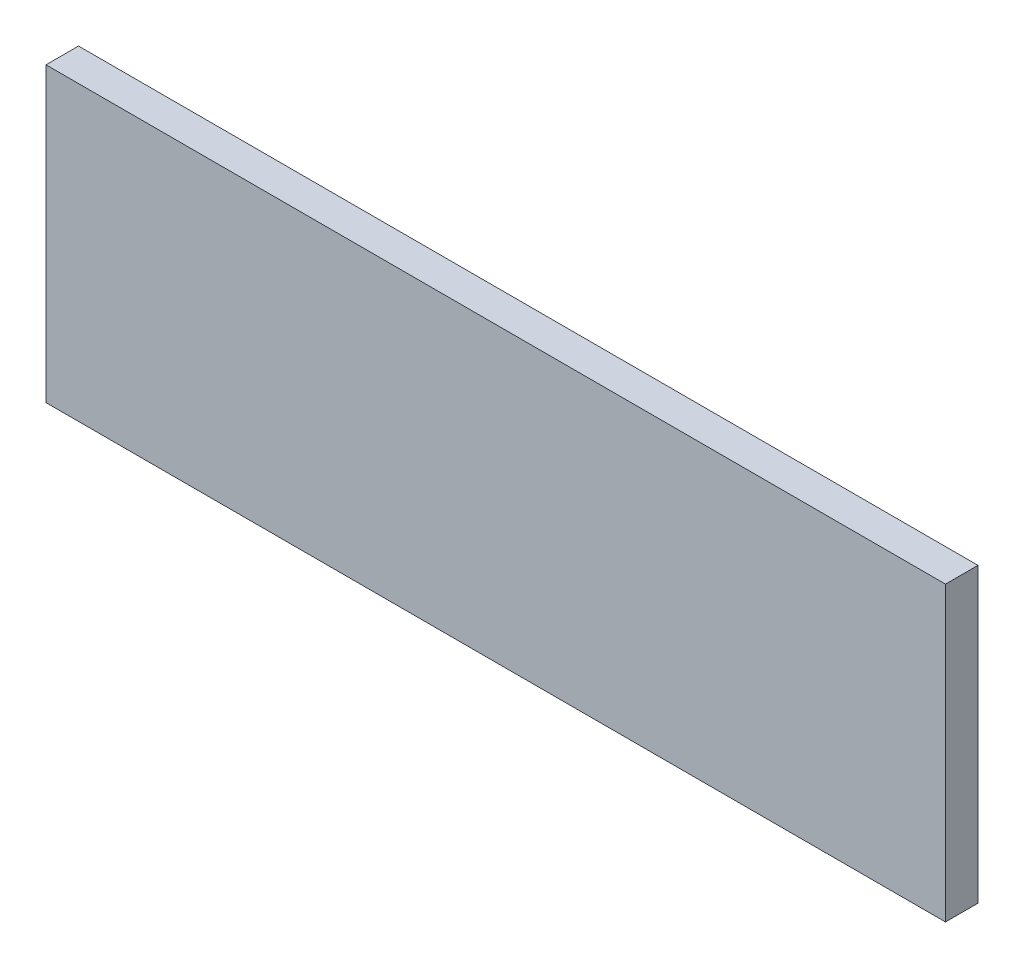
SolidWorks part; units mm, degrees
ref_plane "Front Plane" through (0, 0, 0) normal (0, 0, 1) x (1, 0, 0)
ref_plane "Top Plane" through (0, 0, 0) normal (0, 1, 0) x (1, 0, 0)
ref_plane "Right Plane" through (0, 0, 0) normal (1, 0, 0) x (0, 0, -1)
sketch "Sketch1" plane through (0, 0, 0) normal (0, 0, 1) x (1, 0, 0)
  line L1 (0, 0) -> (41.5, 0)
  line L2 (0, 0) -> (0, 13.5)
  line L3 (0, 13.5) -> (41.5, 13.5)
  line L4 (41.5, 0) -> (41.5, 13.5)
  dimension "D1" = 41.5
  dimension "D2" = 13.5
extrude "Boss-Extrude1" add sketch "Sketch1" along normal blind 1.5
